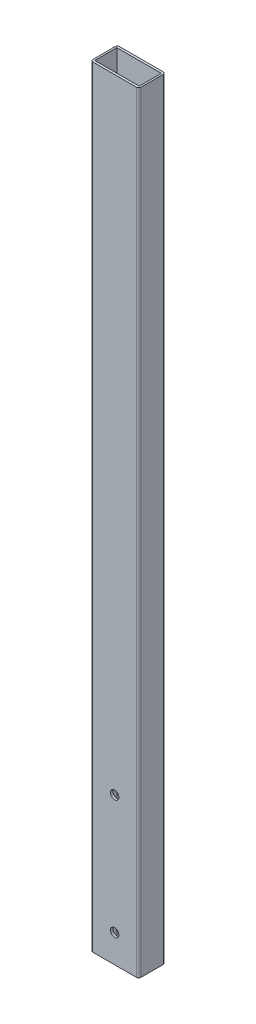
SolidWorks part; units mm, degrees
ref_plane "Front Plane" through (0, 0, 0) normal (0, 0, 1) x (1, 0, 0)
ref_plane "Top Plane" through (0, 0, 0) normal (0, 1, 0) x (1, 0, 0)
ref_plane "Right Plane" through (0, 0, 0) normal (1, 0, 0) x (0, 0, -1)
sketch "Sketch1" plane through (0, 0, 0) normal (0, 1, 0) x (1, 0, 0)
  line L1 (-17.145, -9.525) -> (17.145, -9.525)
  line L2 (-17.145, -9.525) -> (-17.145, 9.525)
  line L3 (-17.145, 9.525) -> (17.145, 9.525)
  line L4 (17.145, -9.525) -> (17.145, 9.525)
  line L5 (-17.145, -9.525) -> (17.145, 9.525) construction
  line L6 (-17.145, 9.525) -> (17.145, -9.525) construction
  line L7 (-15.875, -7.874) -> (15.875, -7.874)
  line L8 (-15.875, -7.874) -> (-15.875, 7.874)
  line L9 (-15.875, 7.874) -> (15.875, 7.874)
  line L10 (15.875, -7.874) -> (15.875, 7.874)
  line L11 (-15.875, -7.874) -> (15.875, 7.874) construction
  line L12 (-15.875, 7.874) -> (15.875, -7.874) construction
  point P0 (0, 0)
  point P6 (0, 0)
  dimension "D1" = 15.748
  dimension "D2" = 19.05
  dimension "D3" = 31.75
  dimension "D4" = 34.29
extrude "Boss-Extrude1" add sketch "Sketch1" along normal blind 550
fillet "Fillet1" radius 1.5 4 edges at (-17.145, 275, -9.525) (17.145, 275, -9.525) (-17.145, 275, 9.525) (17.145, 275, 9.525)
sketch "Sketch2" plane through (0, 0, 9.525) normal (0, 0, 1) x (1, 0, 0)
  line L0 (0, 0) -> (0, 105) construction
  line L1 (-15.645, 0) -> (15.645, 0) construction
  circle A0 centre (0, 105) radius 3
  circle A1 centre (0, 20) radius 3
  dimension "D1" = 6
  dimension "D2" = 85
  dimension "D3" = 20
extrude "Cut-Extrude1" cut sketch "Sketch2" against normal through all both and the other way through all
